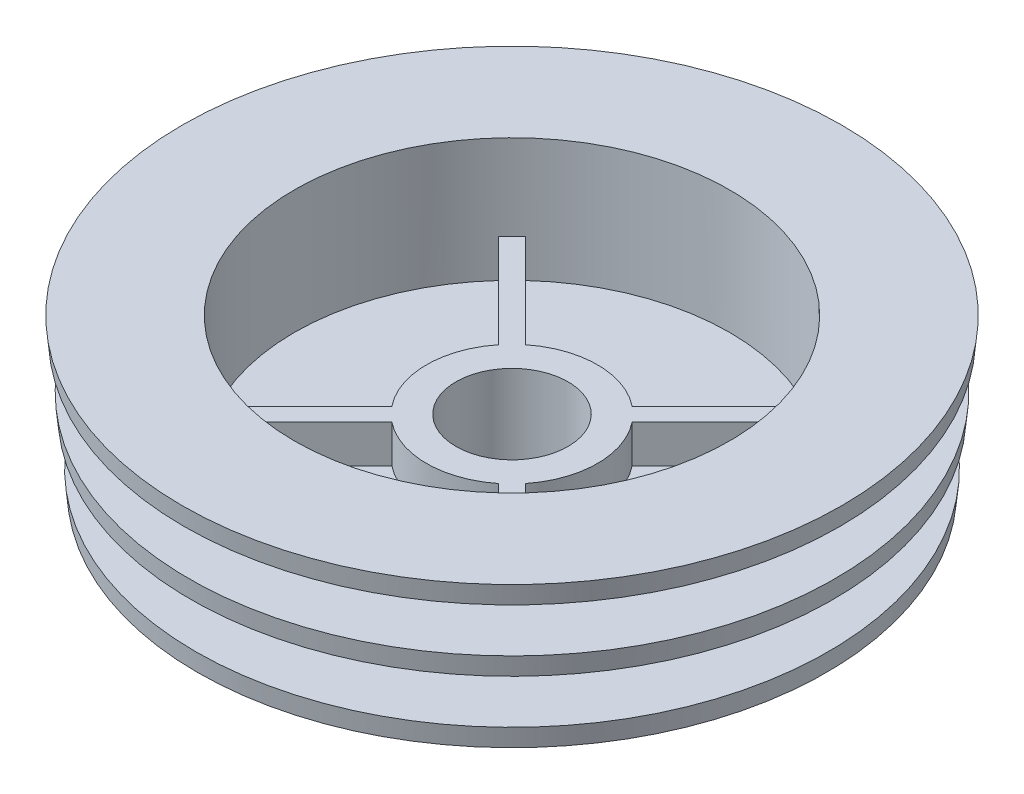
SolidWorks part; units mm, degrees
ref_plane "Plan de face" through (0, 0, 0) normal (0, 0, 1) x (1, 0, 0)
ref_plane "Plan de dessus" through (0, 0, 0) normal (0, 1, 0) x (1, 0, 0)
ref_plane "Plan de droite" through (0, 0, 0) normal (1, 0, 0) x (0, 0, -1)
sketch "Esquisse1" plane through (0, 0, 0) normal (0, 0, 1) x (1, 0, 0)
  line L0 (0, 0) -> (4.6, 0)
  line L1 (4.6, 0) -> (4.6, 6)
  line L2 (4.6, 6) -> (16.55, 6)
  line L3 (16.55, 6) -> (17.35, 14) construction
  line L4 (17.35, 14) -> (0, 14)
  line L5 (0, 0) -> (0, 14) construction
  line L6 (16.55, 6) -> (16.65, 7)
  line L7 (16.65, 7) -> (12.25, 7)
  line L8 (12.25, 7) -> (12.25, 9.5)
  line L9 (12.25, 9.5) -> (16.9, 9.5)
  line L10 (16.9, 9.5) -> (17, 10.5)
  line L11 (17, 10.5) -> (12.25, 10.5)
  line L12 (12.25, 10.5) -> (12.25, 13)
  line L13 (12.25, 13) -> (17.25, 13)
  line L14 (17.25, 13) -> (17.35, 14)
  line L15 (0, 0) -> (0, 14)
  dimension "D1" = 1
  dimension "D2" = 1
  dimension "D3" = 1
  dimension "D4" = 9.2
  dimension "D5" = 14
  dimension "D6" = 8
  dimension "D7" = 34.7
  dimension "D8" = 33.1
  dimension "D9" = 24.5
revolve "Révolution1" add sketch "Esquisse1" angle 360 about L15
sketch "Esquisse2" plane through (0, 0, 0) normal (0, -1, 0) x (1, 0, 0)
  circle A0 centre (0, 0) radius 2.95
extrude "Enlèv. mat.-Extru.1" cut sketch "Esquisse2" against normal blind 3
sketch "Esquisse3" plane through (0, 14, 0) normal (0, 1, 0) x (1, 0, 0)
  circle A0 centre (0, 0) radius 11.45
  dimension "D1" = 22.9
extrude "Enlèv. mat.-Extru.2" cut sketch "Esquisse3" against normal blind 4.5
sketch "Esquisse8" plane through (0, 9.5, 0) normal (0, 1, 0) x (1, 0, 0)
  line L0 (2.8087, 3.5158) -> (7.7351, 8.4422)
  line L1 (3.5158, 2.8087) -> (8.4422, 7.7351)
  line L2 (3.5158, -2.8087) -> (8.4422, -7.7351)
  line L3 (2.8087, -3.5158) -> (7.7351, -8.4422)
  line L4 (-2.8087, -3.5158) -> (-7.7351, -8.4422)
  line L5 (-3.5158, -2.8087) -> (-8.4422, -7.7351)
  line L6 (-3.5158, 2.8087) -> (-8.4422, 7.7351)
  line L7 (-2.8087, 3.5158) -> (-7.7351, 8.4422)
  line L8 (0, 0) -> (12.2683, 12.2683) construction
  line L9 (0, 0) -> (17.35, 0) construction
  arc A0 (-2.8087, 3.5158) -> (2.8087, 3.5158) centre (0, 0) cw
  arc A1 (-7.7351, 8.4422) -> (7.7351, 8.4422) centre (0, 0) cw
  arc A2 (3.5158, 2.8087) -> (3.5158, -2.8087) centre (0, 0) cw
  arc A3 (8.4422, 7.7351) -> (8.4422, -7.7351) centre (0, 0) cw
  arc A4 (2.8087, -3.5158) -> (-2.8087, -3.5158) centre (0, 0) cw
  arc A5 (7.7351, -8.4422) -> (-7.7351, -8.4422) centre (0, 0) cw
  arc A6 (-3.5158, -2.8087) -> (-3.5158, 2.8087) centre (0, 0) cw
  arc A7 (-8.4422, -7.7351) -> (-8.4422, 7.7351) centre (0, 0) cw
  circle A9 centre (0, 0) radius 11.45 construction
  circle A12 centre (0, 0) radius 17.35 construction
  circle A13 centre (0, 0) radius 11.45 construction
  point P21 (0, 0)
  point P34 (0, 0)
  dimension "D3" = 4.5
  dimension "D2" = 1
  dimension "D4" = 45
  dimension "D5" = 1
  dimension "D1" = 4
extrude "Enlèv. mat.-Extru.11" cut sketch "Esquisse8" against normal blind 2
sketch "Esquisse4" plane through (0, 9.5, 0) normal (0, 1, 0) x (1, 0, 0)
  circle A0 centre (0, 0) radius 2.95
  dimension "D1" = 5.9
extrude "Enlèv. mat.-Extru.3" cut sketch "Esquisse4" against normal blind 5.5
sketch "Esquisse6" plane through (0, 4, 0) normal (0, 1, 0) x (1, 0, 0)
  circle A0 centre (0, 0) radius 1.4
  dimension "D1" = 2.8
extrude "Enlèv. mat.-Extru.9" cut sketch "Esquisse6" against normal through all
sketch "Esquisse7" plane through (0, 0, 0) normal (1, 0, 0) x (0, 0, -1)
  line L0 (0, 0) -> (0, 14) construction
  line L1 (17.35, 14) -> (-17.35, 14) construction
  line L2 (-0.5, 12.25) -> (-0.5, 11.25)
  line L3 (0.5, 12.25) -> (0.5, 11.25)
  line L4 (-0.5, 12.25) -> (0.5, 12.25)
  line L5 (0.5, 11.25) -> (-0.5, 11.25)
  line L6 (-12.25, 11.75) -> (12.25, 11.75) construction
  line L7 (-12.25, 13) -> (-12.25, 10.5) construction
  line L8 (12.25, 10.5) -> (12.25, 13) construction
  line L9 (-0.5, 8.75) -> (-0.5, 7.75)
  line L10 (-0.5, 8.75) -> (0.5, 8.75)
  line L11 (0.5, 8.75) -> (0.5, 7.75)
  line L12 (0.5, 7.75) -> (-0.5, 7.75)
  point P15 (-0.5, 11.75)
  dimension "D1" = 1
  dimension "D2" = 1
  dimension "D3" = 2
extrude "Enlèv. mat.-Extru.10" cut sketch "Esquisse7" along normal through all from offset 5
